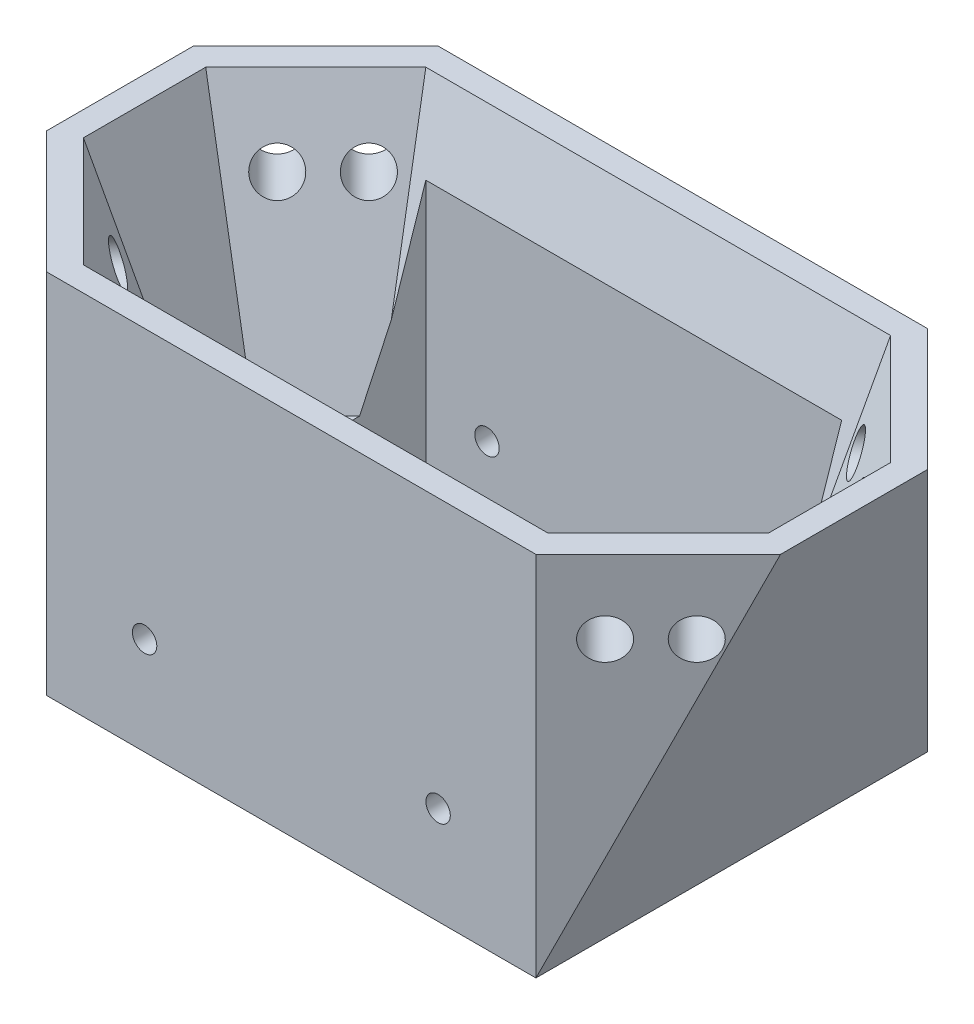
SolidWorks part; units mm, degrees
ref_plane "Front Plane" through (0, 0, 0) normal (0, 0, 1) x (1, 0, 0)
ref_plane "Top Plane" through (0, 0, 0) normal (0, 1, 0) x (1, 0, 0)
ref_plane "Right Plane" through (0, 0, 0) normal (1, 0, 0) x (0, 0, -1)
sketch "Sketch1" plane through (0, 0, 0) normal (0, 1, 0) x (1, 0, 0)
  line L0 (-150, 30) -> (-100, 80)
  line L1 (-100, 80) -> (100, 80)
  line L2 (100, 80) -> (150, 30)
  line L3 (150, 30) -> (150, -30)
  line L4 (150, -30) -> (100, -80)
  line L5 (100, -80) -> (-100, -80)
  line L6 (-100, -80) -> (-150, -30)
  line L7 (-150, -30) -> (-150, 30)
  point P2 (150, -27.1445)
  dimension "D1" = 300
  dimension "D2" = 50
  dimension "D3" = 50
  dimension "D4" = 200
  dimension "D5" = 200
  dimension "D6" = 60
  dimension "D7" = 60
  dimension "D8" = 150
  dimension "D9" = 160
  dimension "D10" = 80
extrude "Boss-Extrude1" add sketch "Sketch1" along normal blind 150
sketch "Sketch2" plane through (0, 0, 0) normal (0, 0, 1) x (1, 0, 0)
  line L0 (-150, 150) -> (-100, 0)
  line L1 (-100, 0) -> (-150, 0)
  line L2 (-150, 0) -> (-150, 150)
  line L3 (100, 0) -> (150, 150)
  line L4 (150, 150) -> (150, 0)
  line L5 (150, 0) -> (100, 0)
extrude "Cut-Extrude1" cut sketch "Sketch2" against normal through all both and the other way through all
sketch "Sketch3" plane through (0, 0, 0) normal (0, 0, 1) x (1, 0, 0)
  line L0 (-85, 200) -> (85, 200)
  line L1 (85, 200) -> (85, 10)
  line L3 (85, 10) -> (-85, 10)
  line L5 (-85, 10) -> (-85, 200)
  line L6 (-100, 0) -> (100, 0) construction
  point P2 (0, 0)
  point P4 (0, 0)
  dimension "D1" = 170
  dimension "D2" = 85
  dimension "D3" = 170
  dimension "D4" = 10
  dimension "D5" = 200
extrude "Cut-Extrude2" cut sketch "Sketch3" against normal mid plane 120
sketch "Sketch4" plane through (0, 150, 0) normal (0, 1, 0) x (1, 0, 0)
  line L0 (-140, -25) -> (-125, -40)
  line L1 (-125, -40) -> (-95, -70)
  line L2 (-95, -70) -> (95, -70)
  line L3 (95, -70) -> (140, -25)
  line L4 (140, -25) -> (140, 25)
  line L5 (140, 25) -> (95, 70)
  line L6 (95, 70) -> (-95, 70)
  line L7 (-95, 70) -> (-140, 25)
  line L8 (-140, 25) -> (-140, -25)
  line L9 (100, 80) -> (-100, 80) construction
  line L10 (-150, 30) -> (-150, -30) construction
  line L11 (-100, 80) -> (-150, 30) construction
  line L13 (-150, -30) -> (-100, -80) construction
  line L14 (100, -80) -> (150, -30) construction
  line L15 (150, 30) -> (100, 80) construction
  point P22 (0, 0)
  point P23 (0, 0)
  dimension "D1" = 10
  dimension "D2" = 150
  dimension "D3" = 10
  dimension "D4" = 290
  dimension "D5" = 190
  dimension "D6" = 190
  dimension "D7" = 45
extrude "Cut-Extrude3" cut sketch "Sketch4" against normal blind 100 draft 18.43
sketch "Sketch5" plane through (-90, 0, 90) normal (-0.7071, 0, 0.7071) x (0.7071, 0, 0.7071)
  line L0 (-84.8528, 150) -> (-14.1421, 150) construction
  line L1 (-14.1421, 150) -> (-14.1421, 0) construction
  circle A0 centre (-60.6421, 120) radius 8.25
  circle A1 centre (-34.1421, 120) radius 8.25
  point P4 (0, 0)
  dimension "D1" = 16.5
  dimension "D2" = 30
  dimension "D3" = 30
  dimension "D4" = 20
  dimension "D5" = 26.5
extrude "Cut-Extrude4" cut sketch "Sketch5" against normal blind 80
mirror "Mirror1" about plane through (0, 0, 0) normal (0, 0, 1) of "Cut-Extrude4"
mirror "Mirror2" about plane through (0, 0, 0) normal (1, 0, 0) of "Mirror1", "Cut-Extrude4"
sketch "Sketch7" plane through (0, 0, 80) normal (0, 0, 1) x (1, 0, 0)
  line L0 (-100, 150) -> (-100, 0) construction
  line L1 (-100, 0) -> (100, 0) construction
  circle A0 centre (-60, 40) radius 5
  circle A1 centre (60, 40) radius 5
  dimension "D1" = 10
  dimension "D2" = 10
  dimension "D3" = 40
  dimension "D4" = 160
  dimension "D5" = 40
  dimension "D6" = 40
extrude "Cut-Extrude5" cut sketch "Sketch7" against normal through all
